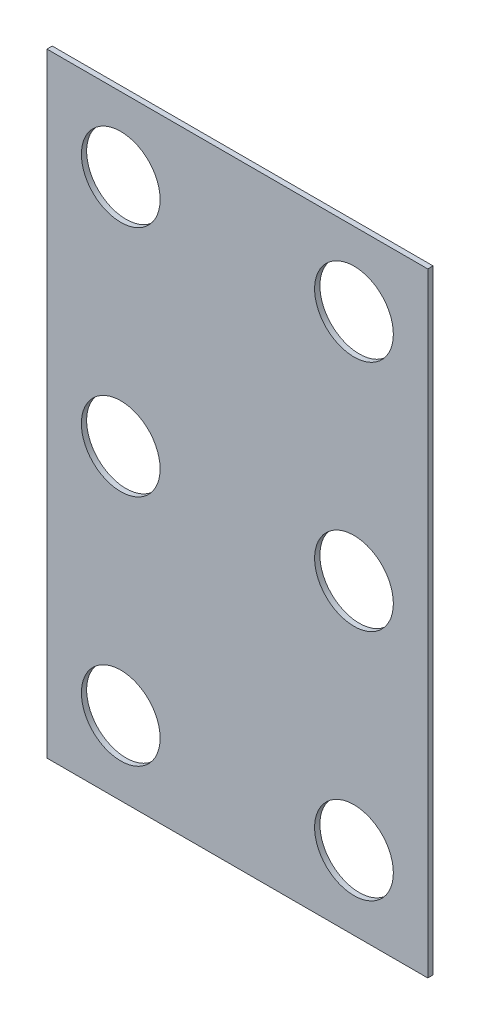
SolidWorks part; units mm, degrees
ref_plane "Front Plane" through (0, 0, 0) normal (0, 0, 1) x (1, 0, 0)
ref_plane "Top Plane" through (0, 0, 0) normal (0, 1, 0) x (1, 0, 0)
ref_plane "Right Plane" through (0, 0, 0) normal (1, 0, 0) x (0, 0, -1)
sketch "Sketch2" plane through (0, 0, 0) normal (0, 0, 1) x (1, 0, 0)
  line L0 (6.43, 50.5) -> (6.43, 53.5) construction
  line L1 (0, 0) -> (33.18, 0)
  line L2 (0, 0) -> (0, 53.5)
  line L3 (0, 53.5) -> (33.18, 53.5)
  line L4 (33.18, 0) -> (33.18, 53.5)
  line L5 (3, 47.07) -> (0, 47.07) construction
  line L6 (16.59, 53.5) -> (16.59, 0) construction
  line L7 (6.43, 3) -> (6.43, 0) construction
  line L8 (30.18, 26.75) -> (33.18, 26.75) construction
  circle A0 centre (6.43, 47.07) radius 3.43
  circle A2 centre (26.75, 47.07) radius 3.43
  circle A3 centre (26.75, 26.75) radius 3.43
  circle A4 centre (26.75, 6.43) radius 3.43
  circle A5 centre (6.43, 26.75) radius 3.43
  circle A6 centre (6.43, 6.43) radius 3.43
  dimension "D1" = 6.86
  dimension "D4" = 3
  dimension "D5" = 20.32
  dimension "D6" = 20.32
  dimension "D3" = 2
  dimension "D2" = 3
extrude "Boss-Extrude1" add sketch "Sketch2" along normal blind 0.46 contours L2 L3 L4 L1
